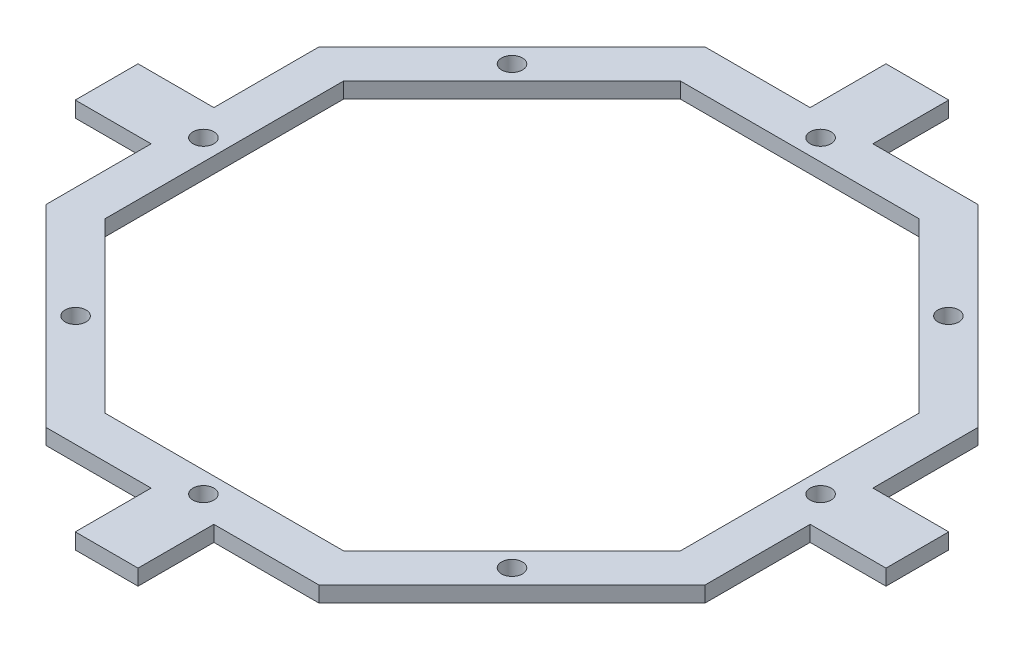
SolidWorks part; units mm, degrees
ref_plane "Front Plane" through (0, 0, 0) normal (0, 0, 1) x (1, 0, 0)
ref_plane "Top Plane" through (0, 0, 0) normal (0, 1, 0) x (1, 0, 0)
ref_plane "Right Plane" through (0, 0, 0) normal (1, 0, 0) x (0, 0, -1)
sketch "Sketch2" plane through (0, 0, 0) normal (0, 1, 0) x (1, 0, 0)
  line L0 (-63, -6) -> (-63, -26.0955)
  line L1 (55, -22.7817) -> (55, 22.7817)
  line L2 (55, 22.7817) -> (22.7817, 55)
  line L3 (22.7817, 55) -> (-22.7817, 55)
  line L4 (-22.7817, 55) -> (-55, 22.7817)
  line L5 (-55, 22.7817) -> (-55, -22.7817)
  line L6 (-55, -22.7817) -> (-22.7817, -55)
  line L7 (-22.7817, -55) -> (22.7817, -55)
  line L8 (22.7817, -55) -> (55, -22.7817)
  line L9 (26.0955, 63) -> (6, 63)
  line L10 (-26.0955, 63) -> (-63, 26.0955)
  line L11 (-63, 26.0955) -> (-63, 6)
  line L12 (-63, -26.0955) -> (-26.0955, -63)
  line L13 (-26.0955, -63) -> (-6, -63)
  line L14 (26.0955, -63) -> (63, -26.0955)
  line L15 (63, -26.0955) -> (63, -6)
  line L16 (63, 26.0955) -> (26.0955, 63)
  line L17 (0, 55) -> (0, 77.5) construction
  line L18 (77.5, -6) -> (77.5, 6)
  line L19 (6, 77.5) -> (-6, 77.5)
  line L20 (6, 77.5) -> (6, 63)
  line L21 (6, 55) -> (-6, 55)
  line L22 (-6, 77.5) -> (-6, 63)
  line L23 (6, 77.5) -> (-6, 55) construction
  line L24 (6, 55) -> (-6, 77.5) construction
  line L25 (77.5, 6) -> (63, 6)
  line L26 (77.5, -6) -> (63, -6)
  line L27 (-6, -77.5) -> (6, -77.5)
  line L28 (6, -77.5) -> (6, -63)
  line L29 (-6, -77.5) -> (-6, -63)
  line L30 (-77.5, 6) -> (-77.5, -6)
  line L31 (-77.5, -6) -> (-63, -6)
  line L32 (-77.5, 6) -> (-63, 6)
  line L33 (-6, 63) -> (-26.0955, 63)
  line L34 (-63, 26.0955) -> (-63, -26.0955) construction
  line L35 (63, 6) -> (63, 26.0955)
  line L36 (26.0955, 63) -> (-26.0955, 63) construction
  line L37 (6, -63) -> (26.0955, -63)
  line L38 (63, -26.0955) -> (63, 26.0955) construction
  line L40 (-26.0955, -63) -> (26.0955, -63) construction
  circle A0 centre (0, 0) radius 55 construction
  point P23 (0, 66.25)
  point P43 (0, 0)
  dimension "D1" = 110
  dimension "D3" = 22.5
  dimension "D4" = 12
  dimension "D2" = 8
  dimension "D5" = 4
extrude "Boss-Extrude1" add sketch "Sketch2" along normal blind 3 contours L28 L37 L14 L15 L26 L18 L25 L35 L16 L9 L20 L19 L22 L33 L10 L11 L32 L30 L31 L0 L12 L13 L29 L27 L8 L7 L6 L5 L4 L3 L2 L1
sketch "Sketch3" plane through (0, 3, 0) normal (0, 1, 0) x (1, 0, 0)
  line L0 (0, 55) -> (0, 63) construction
  line L1 (22.7817, 55) -> (-22.7817, 55) construction
  line L3 (-6, 63) -> (6, 63) construction
  circle A0 centre (0, 59) radius 2
  circle A1 centre (41.7193, 41.7193) radius 2
  circle A2 centre (59, 0) radius 2
  circle A3 centre (41.7193, -41.7193) radius 2
  circle A4 centre (0, -59) radius 2
  circle A5 centre (-41.7193, -41.7193) radius 2
  circle A6 centre (-59, 0) radius 2
  circle A7 centre (-41.7193, 41.7193) radius 2
  point P27 (0, 0)
  dimension "D1" = 4
  dimension "D2" = 8
extrude "Cut-Extrude1" cut sketch "Sketch3" against normal blind 76 and the other way blind 84
